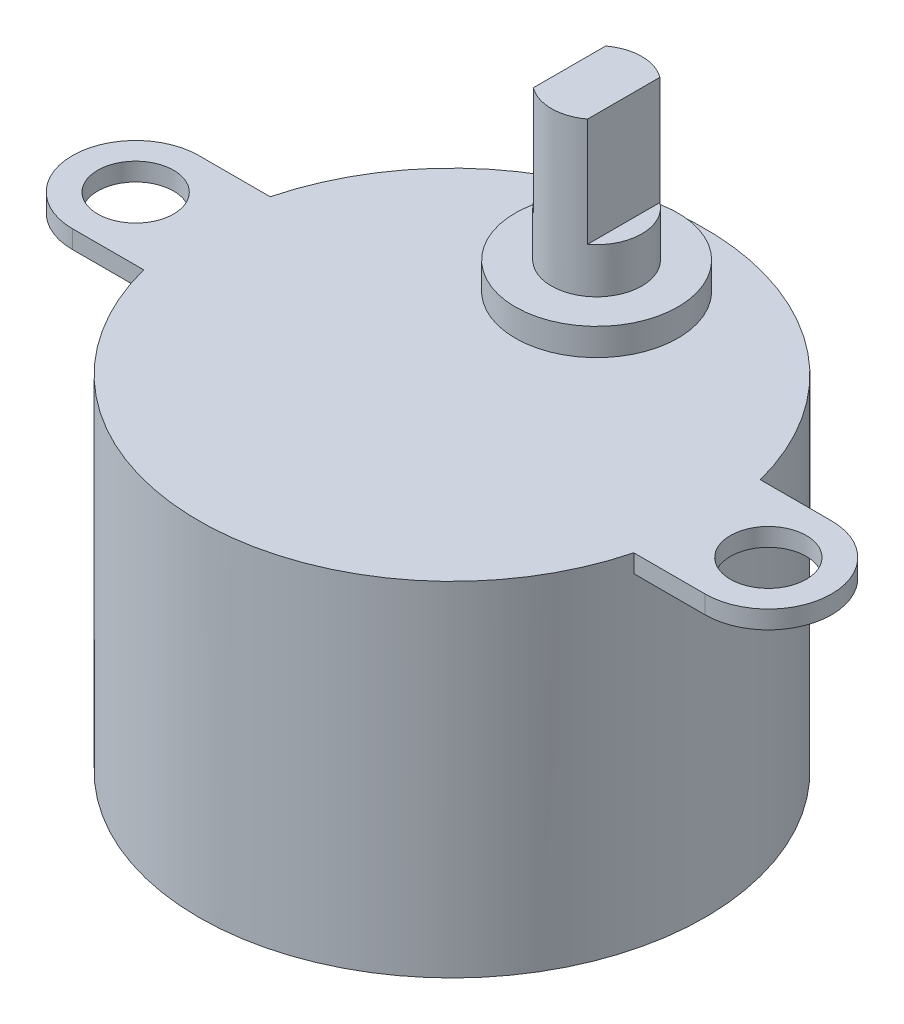
SolidWorks part; units mm, degrees
ref_plane "前视基准面" through (0, 0, 0) normal (0, 0, 1) x (1, 0, 0)
ref_plane "上视基准面" through (0, 0, 0) normal (0, 1, 0) x (1, 0, 0)
ref_plane "右视基准面" through (0, 0, 0) normal (1, 0, 0) x (0, 0, -1)
sketch "草图1" plane through (0, 0, 0) normal (0, 1, 0) x (1, 0, 0)
  circle A0 centre (0, 0) radius 14
  dimension "28" = 28
extrude "凸台-拉伸1" add sketch "草图1" along normal blind 19
sketch "草图2" plane through (0, 19, 0) normal (0, 1, 0) x (1, 0, 0)
  line L0 (-17.5, 0) -> (0, 0) construction
  line L1 (0, 0) -> (17.5, 0) construction
  line L2 (-17.5, 0) -> (17.5, 0) construction
  line L3 (-17.5, 3.5) -> (17.5, 3.5)
  line L4 (-17.5, -3.5) -> (17.5, -3.5)
  circle A0 centre (-17.5, 0) radius 2.1
  circle A1 centre (17.5, 0) radius 2.1
  arc A2 (-17.5, 3.5) -> (-17.5, -3.5) centre (-17.5, 0) ccw
  arc A3 (17.5, -3.5) -> (17.5, 3.5) centre (17.5, 0) ccw
  point P4 (0, 0)
  dimension "D1" = 4.2
  dimension "D3" = 3.5
  dimension "D2" = 35
extrude "凸台-拉伸2" add sketch "草图2" against normal blind 1
sketch "草图3" plane through (0, 19, 0) normal (0, 1, 0) x (1, 0, 0)
  circle A0 centre (0, 8) radius 4.5
  dimension "D2" = 9
  dimension "D1" = 8
extrude "凸台-拉伸3" add sketch "草图3" along normal blind 1.5
sketch "草图4" plane through (0, 20.5, 0) normal (0, 1, 0) x (1, 0, 0)
  circle A0 centre (0, 8) radius 2.5
  dimension "D1" = 5
extrude "凸台-拉伸4" add sketch "草图4" along normal blind 2.5
sketch "草图5" plane through (0, 23, 0) normal (0, 1, 0) x (1, 0, 0)
  line L0 (0, 6) -> (0, 8) construction
  line L2 (-1.5, 10) -> (-1.5, 6)
  line L4 (1.5, 10) -> (1.5, 6)
  arc A0 (-1.5, 6) -> (1.5, 6) centre (0, 8) ccw
  arc A1 (1.5, 10) -> (-1.5, 10) centre (0, 8) ccw
  dimension "D2" = 5
  dimension "D1" = 3
extrude "凸台-拉伸5" add sketch "草图5" along normal blind 6
